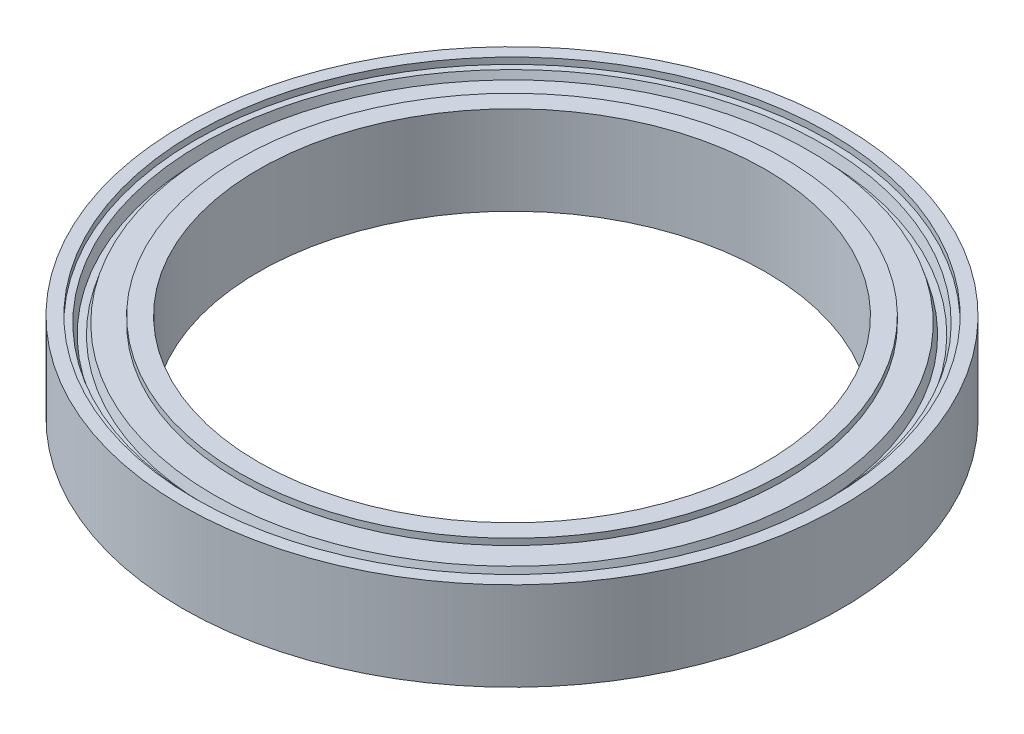
SolidWorks part; units mm, degrees
material "06ХН28МДТ ГОСТ 4543-71"
ref_plane "Спереди" through (0, 0, 0) normal (0, 0, 1) x (1, 0, 0)
ref_plane "Сверху" through (0, 0, 0) normal (0, 1, 0) x (1, 0, 0)
ref_plane "Справа" through (0, 0, 0) normal (1, 0, 0) x (0, 0, -1)
other "Configuration Table"
sketch "Эскиз1" plane through (0, 0, 0) normal (0, 1, 0) x (1, 0, 0)
  circle A0 centre (0, 0) radius 20
  circle A1 centre (0, 0) radius 26
  dimension "D1" = 52
  dimension "D2" = 40
extrude "Бобышка-Вытянуть1" add sketch "Эскиз1" along normal blind 7
sketch "Эскиз2" plane through (0, 7, 0) normal (0, 1, 0) x (1, 0, 0)
  circle A0 centre (0, 0) radius 21.5
  circle A1 centre (0, 0) radius 25
  dimension "D1" = 50
  dimension "D2" = 43
extrude "Вырез-Вытянуть1" cut sketch "Эскиз2" against normal blind 0.5
sketch "Эскиз3" plane through (0, 6.5, 0) normal (0, 1, 0) x (1, 0, 0)
  circle A0 centre (0, 0) radius 24.5
  circle A1 centre (0, 0) radius 23.5
  dimension "D1" = 47
  dimension "D2" = 49
extrude "Вырез-Вытянуть2" cut sketch "Эскиз3" against normal blind 0.8 draft 17
